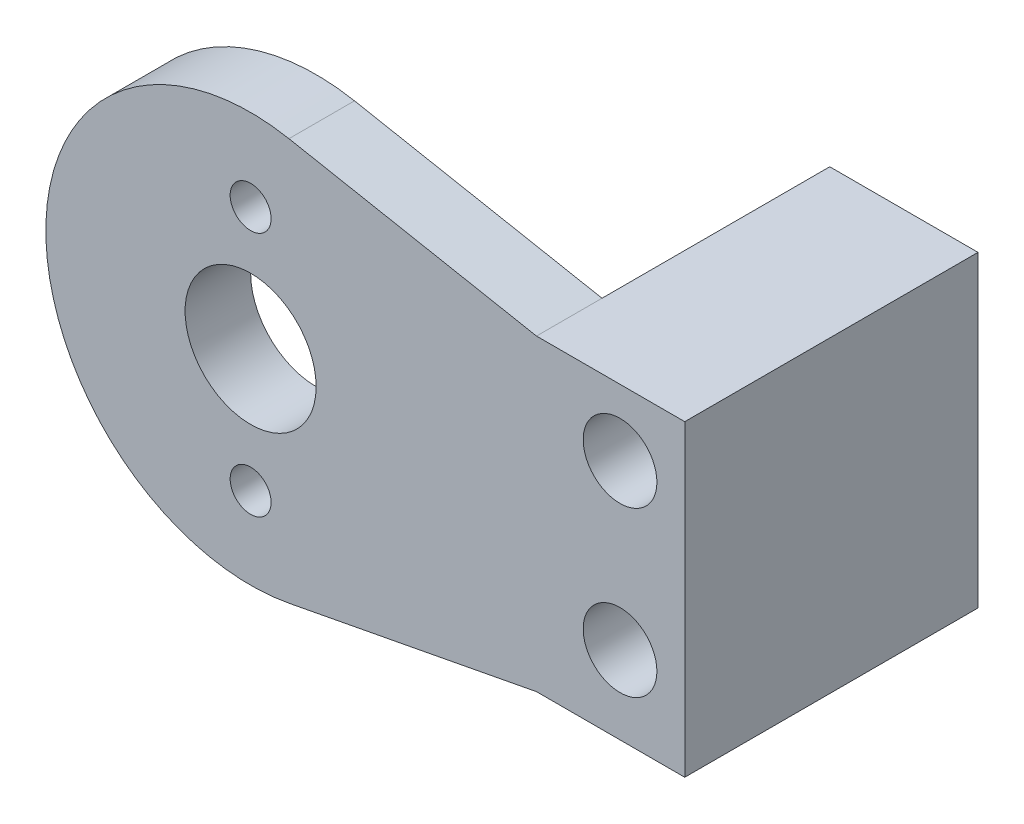
SolidWorks part; units mm, degrees
material "PLA"
ref_plane "Front Plane" through (0, 0, 0) normal (0, 0, 1) x (1, 0, 0)
ref_plane "Top Plane" through (0, 0, 0) normal (0, 1, 0) x (1, 0, 0)
ref_plane "Right Plane" through (0, 0, 0) normal (1, 0, 0) x (0, 0, -1)
ref_plane "Plane1" through (0, 0, 79.9405) normal (0, 0, -1) x (-1, 0, 0)
sketch "Sketch1" plane through (0, 0, 79.9405) normal (0, 0, -1) x (-1, 0, 0)
  line L0 (9.05, 0) -> (24.1604, -2.8791)
  line L1 (9.05, 18.8) -> (24.1604, 21.6791)
  line L25 (9.05, 18.8) -> (0, 18.8)
  line L26 (0, 18.8) -> (0, 0)
  line L27 (0, 0) -> (9.05, 0)
  line L89 (114.6938, 17.2312) -> (114.6938, -10.9376) construction
  line L90 (0, 9.4) -> (-1.8294, 9.4) construction
  arc A0 (24.1604, -2.8791) -> (24.1604, 21.6791) centre (26.5, 9.4) ccw
  dimension "D7" = 25
  dimension "D1" = 18.8
  dimension "D3" = 9.05
  dimension "D4" = 9.05
  dimension "D5" = 9.4
  dimension "D6" = 0
  dimension "D8" = 26.5
extrude "Boss-Extrude1" add sketch "Sketch1" against normal blind 4
sketch "Sketch2" plane through (0, 0, 79.9405) normal (0, 0, -1) x (-1, 0, 0)
  line L0 (9.05, 0) -> (0, 0)
  line L1 (0, 0) -> (0, 18.8)
  line L2 (0, 18.8) -> (9.05, 18.8)
  line L3 (9.05, 18.8) -> (9.05, 0)
  dimension "D1" = 9.05
  dimension "D2" = 18.8
extrude "Boss-Extrude2" add sketch "Sketch2" along normal blind 13.9
sketch "Sketch3" plane through (0, 0, 83.9405) normal (0, 0, 1) x (1, 0, 0)
  line L0 (-9.05, 18.8) -> (0, 18.8) construction
  line L1 (0, 18.8) -> (0, 0) construction
  line L2 (0, 0) -> (-9.05, 0) construction
  circle A0 centre (-26.5, 9.4) radius 4
  circle A1 centre (-3.95, 14.75) radius 2.25
  circle A2 centre (-3.95, 4.75) radius 2.25
  circle A3 centre (-26.5, 16.9) radius 1.25
  circle A4 centre (-26.5, 1.9) radius 1.25
  arc A5 (-24.1604, 21.6791) -> (-24.1604, -2.8791) centre (-26.5, 9.4) ccw construction
  dimension "D4" = 4.5
  dimension "D5" = 4.5
  dimension "D6" = 8
  dimension "D7" = 2.5
  dimension "D8" = 2.5
  dimension "D2" = 3.95
  dimension "D3" = 10
  dimension "D9" = 1.9
  dimension "D10" = 1.9
  dimension "D11" = 4.75
extrude "Cut-Extrude1" cut sketch "Sketch3" against normal blind 30
